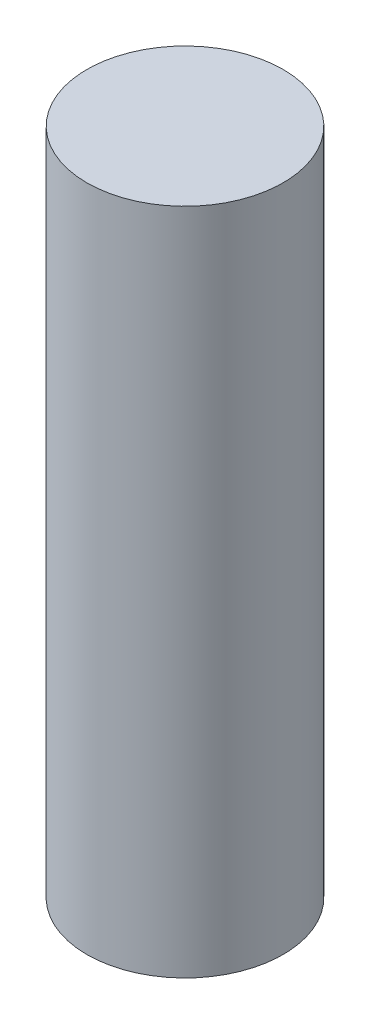
SolidWorks part; units mm, degrees
ref_plane "Front Plane" through (0, 0, 0) normal (0, 0, 1) x (1, 0, 0)
ref_plane "Top Plane" through (0, 0, 0) normal (0, 1, 0) x (1, 0, 0)
ref_plane "Right Plane" through (0, 0, 0) normal (1, 0, 0) x (0, 0, -1)
sketch "Sketch1" plane through (0, 0, 0) normal (0, 1, 0) x (1, 0, 0)
  circle A0 centre (0, 0) radius 13
  dimension "D1" = 26
extrude "Boss-Extrude1" add sketch "Sketch1" along normal blind 88.5
